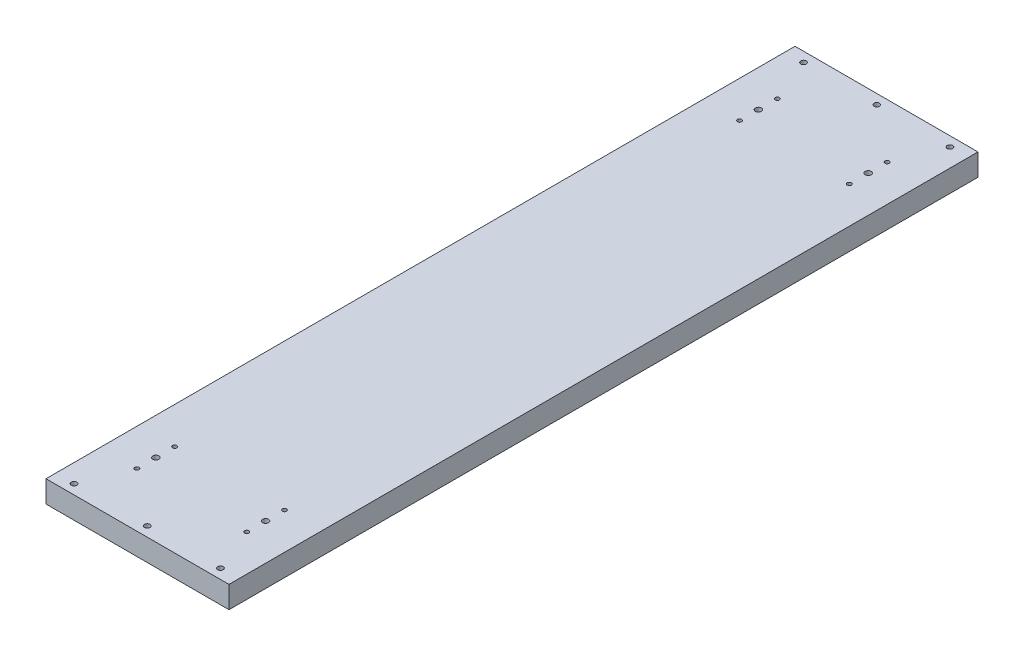
SolidWorks part; units mm, degrees
ref_plane "Front Plane" through (0, 0, 0) normal (0, 0, 1) x (1, 0, 0)
ref_plane "Top Plane" through (0, 0, 0) normal (0, 1, 0) x (1, 0, 0)
ref_plane "Right Plane" through (0, 0, 0) normal (1, 0, 0) x (0, 0, -1)
other "Bounding Box"
ref_plane "Default Plane" through (75, 9, -307) normal (-1, 0, 0) x (0, 0, 1)
sketch "Sketch1" plane through (0, 0, 0) normal (0, 1, 0) x (1, 0, 0)
  line L0 (-75, 307) -> (75, -307) construction
  line L1 (-75, 307) -> (75, 307)
  line L2 (-75, 307) -> (-75, -307)
  line L3 (-75, -307) -> (75, -307)
  line L4 (75, 307) -> (75, -307)
  line L5 (75, 307) -> (-75, -307) construction
  point P0 (0, 0)
  dimension "D1" = 150
  dimension "D2" = 614
extrude "Boss-Extrude1" add sketch "Sketch1" along normal mid plane 18 contours L4 L3 L2 L1
hole_wizard "CSK for #8 Flat Head Machine Screw (100)1" positions "Sketch2" profile "Sketch3" countersink size "#8" standard "ANSI Inch" end condition through all
sketch "Sketch2" plane through (-75, -9, 0) normal (0, -1, 0) x (0, 0, -1)
  line L3 (-307, 0) -> (-307, 150) construction
  line L4 (307, 150) -> (-307, 150) construction
  point P0 (-299, 135)
  point P9 (-299, 75)
  point P14 (-299, 15)
  dimension "D1" = 15
  dimension "D2" = 60
  dimension "D3" = 60
  dimension "D4" = 8
sketch "Sketch3" plane through (60, -9, 299) normal (1, 0, 0) x (0, 0, -1)
  line L0 (0, 0) -> (0, 18)
  line L1 (0, 18) -> (2.2479, 18)
  line L2 (2.2479, 18) -> (2.2479, 1.6518)
  line L3 (2.2479, 1.6518) -> (4.2164, 0)
  line L5 (4.2164, 0) -> (0, 0)
  line L6 (-2.2479, 1.6518) -> (-4.2164, 0) construction
  line L11 (0, -6.35) -> (0, 107.95) construction
  dimension "Thru Hole Dia." = 4.4958
  dimension "Thru Hole Depth" = 18
  dimension "Near C'Sink Dia." = 8.4328
  dimension "Near C'Sink Angle" = 100
mirror "Mirror1" about plane through (0, 0, 0) normal (0, 0, 1) of "CSK for #8 Flat Head Machine Screw (100)1"
hole_wizard "#8-36 Tapped Hole1" positions "Sketch6" profile "Sketch5" tap size "#8-36" standard "ANSI Inch" end condition through all
sketch "Sketch6" plane through (0, -9, 0) normal (0, -1, 0) x (-1, 0, 0)
  line L0 (45, -262.5) -> (45, -231.5) construction
  line L2 (75, 307) -> (75, -307) construction
  line L3 (75, -307) -> (-75, -307) construction
  point P0 (45, -262.5)
  point P2 (45, -231.5)
  point P10 (45, -247)
  dimension "D1" = 30
  dimension "D2" = 60
  dimension "D3" = 31
sketch "Sketch5" plane through (-45, -9, 262.5) normal (1, 0, 0) x (0, 0, -1)
  line L0 (0, 0) -> (0, 18)
  line L1 (0, 18) -> (1.7272, 18)
  line L2 (1.7272, 18) -> (1.7272, 0)
  line L5 (1.7272, 0) -> (0, 0)
  line L11 (0, -6.35) -> (0, 107.95) construction
  dimension "Thru Tap Drill Dia." = 3.4544
  dimension "Thru Tap Drill Depth" = 18
cosmetic thread "Hole Thread1" parameters "D2"=4.1656
cosmetic thread "Hole Thread2" parameters "D2"=4.1656
hole_wizard "#8 Clearance Hole1" positions "Sketch9" profile "Sketch8" hole size "#8" standard "ANSI Inch" end condition through all
sketch "Sketch9" plane through (0, -9, 0) normal (0, -1, 0) x (-1, 0, 0)
  line L0 (45, -231.5) -> (45, -262.5) construction
  point P0 (45, -247)
sketch "Sketch8" plane through (-45, -9, 247) normal (1, 0, 0) x (0, 0, -1)
  line L0 (0, 0) -> (0, 18)
  line L1 (0, 18) -> (2.4574, 18)
  line L2 (2.4574, 18) -> (2.4574, 0)
  line L5 (2.4574, 0) -> (0, 0)
  line L11 (0, -6.35) -> (0, 107.95) construction
  dimension "Thru Hole Dia." = 4.9149
  dimension "Thru Hole Depth" = 18
mirror "Mirror2" about plane through (0, 0, 0) normal (0, 0, 1) of "#8-36 Tapped Hole1", "#8 Clearance Hole1" second plane through (0, 0, 0) second plane normal (1, 0, 0)
cosmetic thread "Hole Thread3" parameters "D2"=4.1656
cosmetic thread "Hole Thread4" parameters "D2"=4.1656
cosmetic thread "Hole Thread5" parameters "D2"=4.1656
cosmetic thread "Hole Thread6" parameters "D2"=4.1656
cosmetic thread "Hole Thread7" parameters "D2"=4.1656
cosmetic thread "Hole Thread8" parameters "D2"=4.1656
